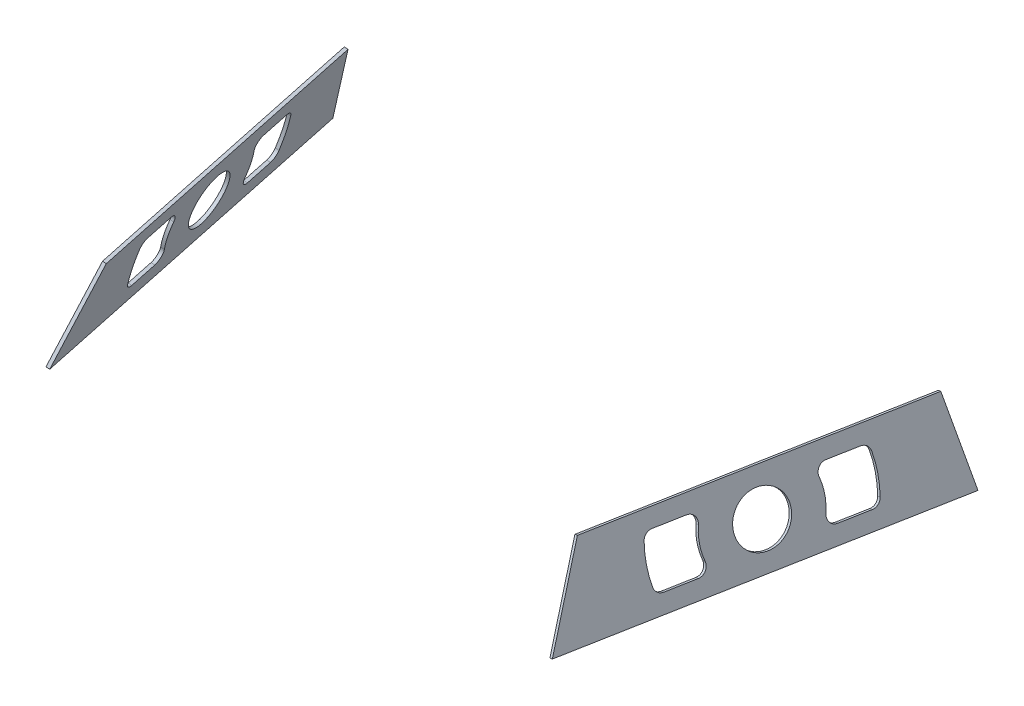
SolidWorks part; units mm, degrees
material "AISI 4130 Steel, normalized at 870C"
ref_plane "Front Plane" through (0, 0, 0) normal (0, 0, 1) x (1, 0, 0)
ref_plane "Top Plane" through (0, 0, 0) normal (0, 1, 0) x (1, 0, 0)
ref_plane "Right Plane" through (0, 0, 0) normal (1, 0, 0) x (0, 0, -1)
ref_plane "Plane1" through (-657.6469, 201.0249, 134.8093) normal (-0.9385, 0.2869, 0.1924) x (0.1851, -0.0527, 0.9813)
sketch "Sketch1" plane through (-657.6469, 201.0249, 134.8093) normal (-0.9385, 0.2869, 0.1924) x (0.1851, -0.0527, 0.9813)
  line L0 (1392.5449, 794.1607) -> (1385.5068, 743.8209)
  line L1 (1385.5068, 743.8209) -> (1606.0783, 753.0877)
  line L2 (1606.0783, 753.0877) -> (1580.8715, 802.0728)
  line L3 (1580.8715, 802.0728) -> (1392.5449, 794.1607)
  line L6 (1409.8147, 798.5353) -> (1433.754, 799.5411) construction
  line L7 (1581.1847, 765.6997) -> (1613.0162, 767.037) construction
  line L9 (1433.6512, 1088.1712) -> (1865.9619, 248.0468) construction
  line L10 (1433.6512, 1088.1712) -> (1319.1623, 269.2957) construction
  line L11 (1562.7965, 837.7154) -> (1396.9812, 828.0069) construction
  point P20 (1479.8888, 832.8612)
  dimension "D1" = 50
  dimension "D2" = 35
extrude "Boss-Extrude1" add sketch "Sketch1" along normal blind 2 from offset 12.7
sketch "Sketch3" plane through (-657.6469, 201.0249, 134.8093) normal (-0.9385, 0.2869, 0.1924) x (0.1851, -0.0527, 0.9813)
  line L0 (1389.0258, 768.9908) -> (1593.4749, 777.5803) construction
  line L1 (1392.5449, 794.1607) -> (1385.5068, 743.8209) construction
  line L2 (1606.0783, 753.0877) -> (1580.8715, 802.0728) construction
  line L3 (1486.7082, 798.1168) -> (1495.7925, 748.4543) construction
  line L4 (1580.8715, 802.0728) -> (1392.5449, 794.1607) construction
  line L5 (1385.5068, 743.8209) -> (1606.0783, 753.0877) construction
  circle A0 centre (1491.2504, 773.2856) radius 15
  dimension "D1" = 30
extrude "Cut-Extrude4" cut sketch "Sketch3" along normal through all both and the other way through all contours A0
sketch "Sketch4" plane through (-671.4423, 205.2418, 137.6372) normal (-0.9385, 0.2869, 0.1924) x (0.1863, -0.0487, 0.9813)
  line L0 (1457.7462, 780.7436) -> (1439.8179, 780.0645)
  line L1 (1458.8817, 750.7651) -> (1440.9534, 750.086)
  line L2 (1529.9786, 783.4796) -> (1547.9069, 784.1586)
  line L3 (1531.1141, 753.5011) -> (1549.0424, 754.1801)
  line L4 (1584.1694, 795.5393) -> (1395.8117, 788.4048) construction
  line L5 (1458.8817, 750.7651) -> (1531.1141, 753.5011) construction
  line L6 (1388.5658, 738.0945) -> (1609.1737, 746.4506) construction
  line L7 (1457.7462, 780.7436) -> (1529.9786, 783.4796) construction
  arc A1 (1435.0596, 775.7904) -> (1435.8854, 753.9879) centre (1494.4302, 767.1223) ccw
  arc A2 (1526.0589, 759.6475) -> (1525.4028, 776.9684) centre (1494.4302, 767.1223) ccw
  arc A3 (1553.8007, 758.4542) -> (1552.9749, 780.2568) centre (1494.4302, 767.1223) ccw
  arc A4 (1549.0424, 754.1801) -> (1553.8007, 758.4542) centre (1548.8532, 759.1766) ccw
  arc A5 (1547.9069, 784.1586) -> (1552.9749, 780.2568) centre (1548.0962, 779.1622) cw
  arc A9 (1440.9534, 750.086) -> (1435.8854, 753.9879) centre (1440.7642, 755.0824) cw
  arc A11 (1439.8179, 780.0645) -> (1435.0596, 775.7904) centre (1440.0072, 775.0681) ccw
  arc A12 (1462.8014, 774.5972) -> (1463.4575, 757.2763) centre (1494.4302, 767.1223) ccw
  arc A13 (1458.8817, 750.7651) -> (1463.4575, 757.2763) centre (1458.6925, 755.7615) ccw
  arc A14 (1462.8014, 774.5972) -> (1457.7462, 780.7436) centre (1457.9355, 775.7472) ccw
  arc A15 (1526.0589, 759.6475) -> (1531.1141, 753.5011) centre (1530.9249, 758.4975) ccw
  arc A16 (1525.4028, 776.9684) -> (1529.9786, 783.4796) centre (1530.1679, 778.4831) cw
  circle A20 centre (1494.4302, 767.1223) radius 15 construction
  point P16 (1553.0511, 754.332)
  point P30 (1436.9448, 749.9342)
  point P36 (1435.8093, 779.9127)
  dimension "D1" = 32.5
  dimension "D2" = 120
  dimension "D5" = 5
  dimension "D6" = 32.5
  dimension "D8" = 5
  dimension "D7" = 5
  dimension "D9" = 5
  dimension "D10" = 5
  dimension "D3" = 10
  dimension "D4" = 10
extrude "Cut-Extrude5" cut sketch "Sketch4" against normal through all both and the other way through all
sketch "Sketch5" plane through (-671.4423, 205.2418, 137.6372) normal (-0.9385, 0.2869, 0.1924) x (0.1863, -0.0487, 0.9813)
  circle A0 centre (1514.761, 798.8511) radius 19.9624 construction
  circle A1 centre (1514.761, 798.8511) radius 19.9624
  circle A2 centre (1514.7615, 798.8234) radius 14.4728 construction
  circle A3 centre (1514.7615, 798.8234) radius 14.4728
split line "Split Line1" [suppressed]
mirror "Mirror2" about plane through (0, 0, 0) normal (1, 0, 0) of bodies 104
